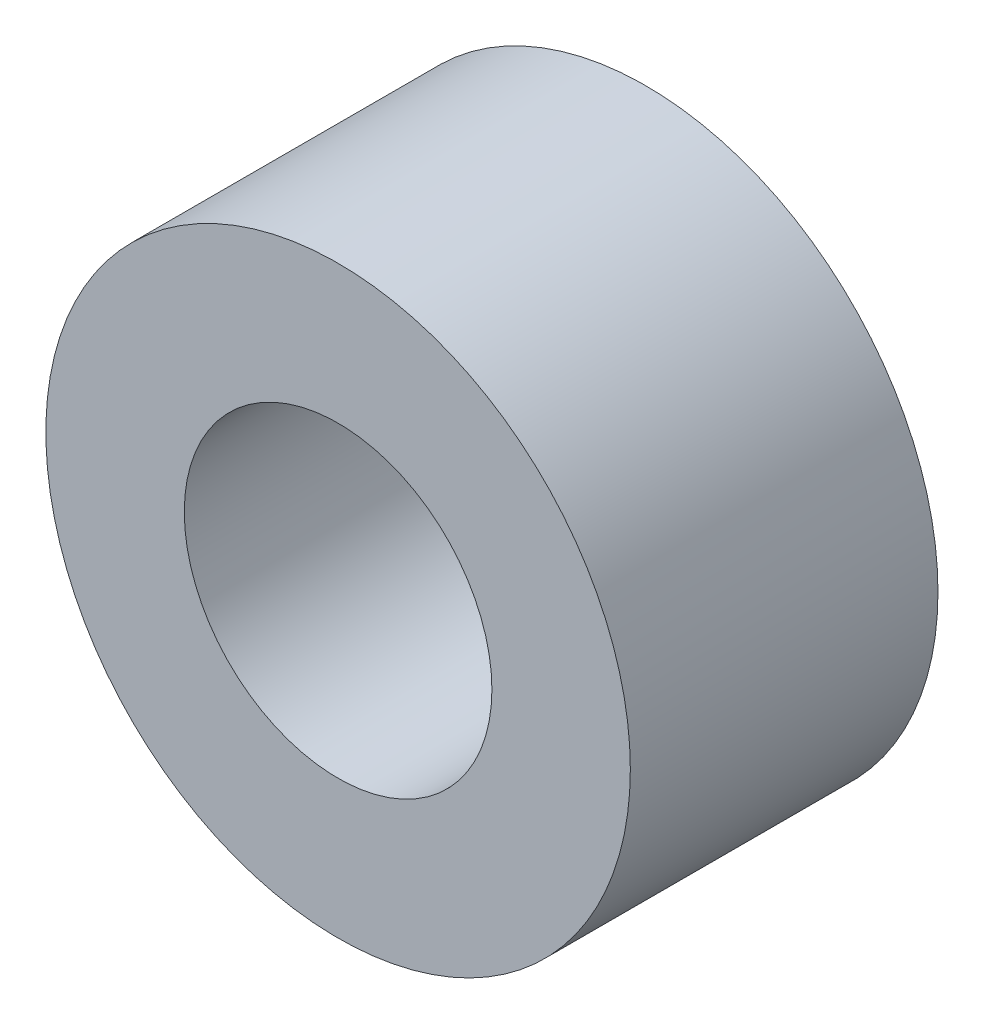
SolidWorks part; units mm, degrees
ref_plane "前视基准面" through (0, 0, 0) normal (0, 0, 1) x (1, 0, 0)
ref_plane "上视基准面" through (0, 0, 0) normal (0, 1, 0) x (1, 0, 0)
ref_plane "右视基准面" through (0, 0, 0) normal (1, 0, 0) x (0, 0, -1)
sketch "草图1" plane through (0, 0, 0) normal (0, 0, 1) x (1, 0, 0)
  circle A0 centre (0, 0) radius 4.75
  circle A1 centre (0, 0) radius 2.5
  dimension "D1" = 5
  dimension "D2" = 9.5
extrude "凸台-拉伸1" add sketch "草图1" along normal blind 5 contours A1 | A0 A1
sketch "草图2" plane through (0, 0, 5) normal (0, 0, 1) x (1, 0, 0)
  circle A0 centre (0, 0) radius 2.5
  dimension "D1" = 5
extrude "切除-拉伸1" cut sketch "草图2" against normal blind 5
